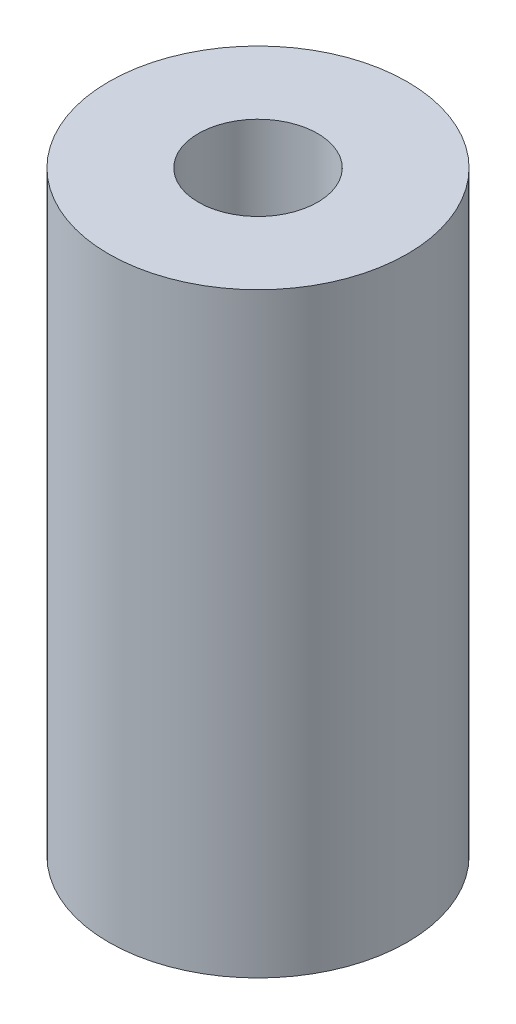
SolidWorks part; units mm, degrees
material "Delrin 2700 NC010, Low Viscosity Acetal Copolymer (SS)"
ref_plane "Front Plane" through (0, 0, 0) normal (0, 0, 1) x (1, 0, 0)
ref_plane "Top Plane" through (0, 0, 0) normal (0, 1, 0) x (1, 0, 0)
ref_plane "Right Plane" through (0, 0, 0) normal (1, 0, 0) x (0, 0, -1)
sketch "Sketch1" plane through (0, 0, 0) normal (0, 1, 0) x (1, 0, 0)
  circle A0 centre (0, 0) radius 15.9004
  dimension "D1" = 31.8008
extrude "Boss-Extrude1" add sketch "Sketch1" along normal blind 63.5
sketch "Sketch2" plane through (0, 63.5, 0) normal (0, 1, 0) x (1, 0, 0)
  circle A0 centre (0, 0) radius 6.35
  dimension "D1" = 12.7
extrude "Cut-Extrude1" cut sketch "Sketch2" against normal through all
